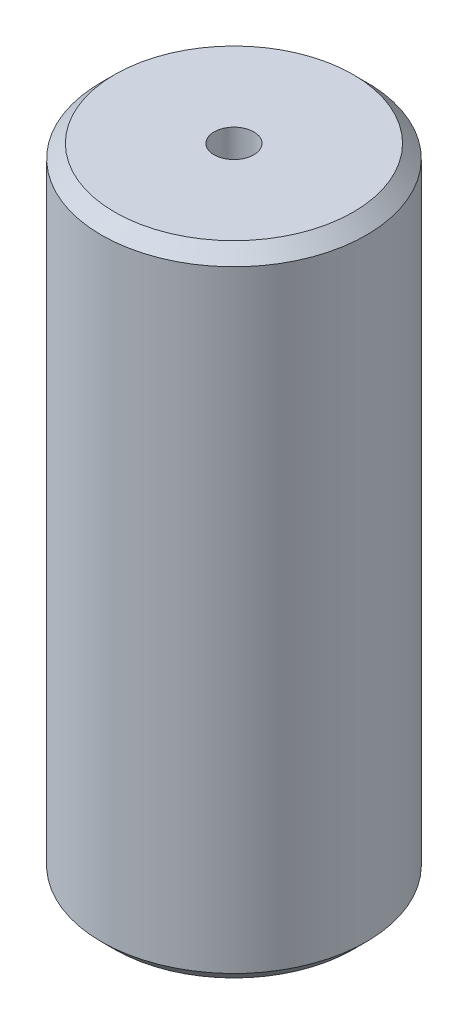
SolidWorks part; units mm, degrees
ref_plane "Front Plane" through (0, 0, 0) normal (0, 0, 1) x (1, 0, 0)
ref_plane "Top Plane" through (0, 0, 0) normal (0, 1, 0) x (1, 0, 0)
ref_plane "Right Plane" through (0, 0, 0) normal (1, 0, 0) x (0, 0, -1)
sketch "Sketch1" plane through (0, 0, 0) normal (0, 1, 0) x (1, 0, 0)
  circle A0 centre (0, 0) radius 10
  circle A1 centre (0, 0) radius 1.5
  dimension "D1" = 3
  dimension "D2" = 20
extrude "Boss-Extrude1" add sketch "Sketch1" along normal blind 48.2
chamfer "Chamfer1" distance 1 angle 45 2 edges at (0, 0, 10) (0, 48.2, 10)
